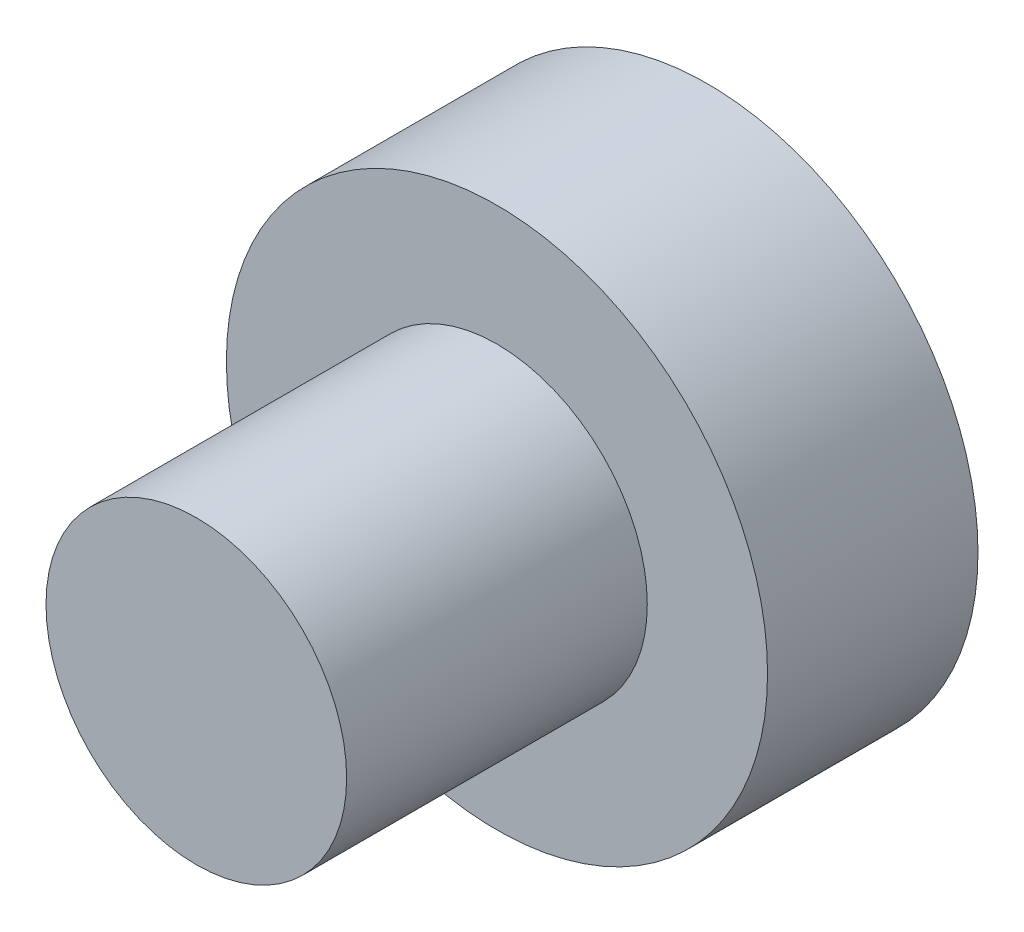
SolidWorks part; units mm, degrees
ref_plane "Front Plane" through (0, 0, 0) normal (0, 0, 1) x (1, 0, 0)
ref_plane "Top Plane" through (0, 0, 0) normal (0, 1, 0) x (1, 0, 0)
ref_plane "Right Plane" through (0, 0, 0) normal (1, 0, 0) x (0, 0, -1)
sketch "Sketch1" plane through (0, 0, 0) normal (0, 0, 1) x (1, 0, 0)
  circle A0 centre (0, 0) radius 5
  dimension "D1" = 10
extrude "Boss-Extrude1" add sketch "Sketch1" along normal blind 10
sketch "Sketch2" plane through (0, 0, 0) normal (0, 0, -1) x (-1, 0, 0)
  circle A0 centre (0, 0) radius 9
  dimension "D1" = 18
extrude "Boss-Extrude2" add sketch "Sketch2" along normal blind 7
sketch "Sketch3" plane through (0, 0, -7) normal (0, 0, -1) x (-1, 0, 0)
  circle A0 centre (0, 0) radius 5.1
  dimension "D1" = 10.2
extrude "Cut-Extrude1" cut sketch "Sketch3" against normal blind 6
